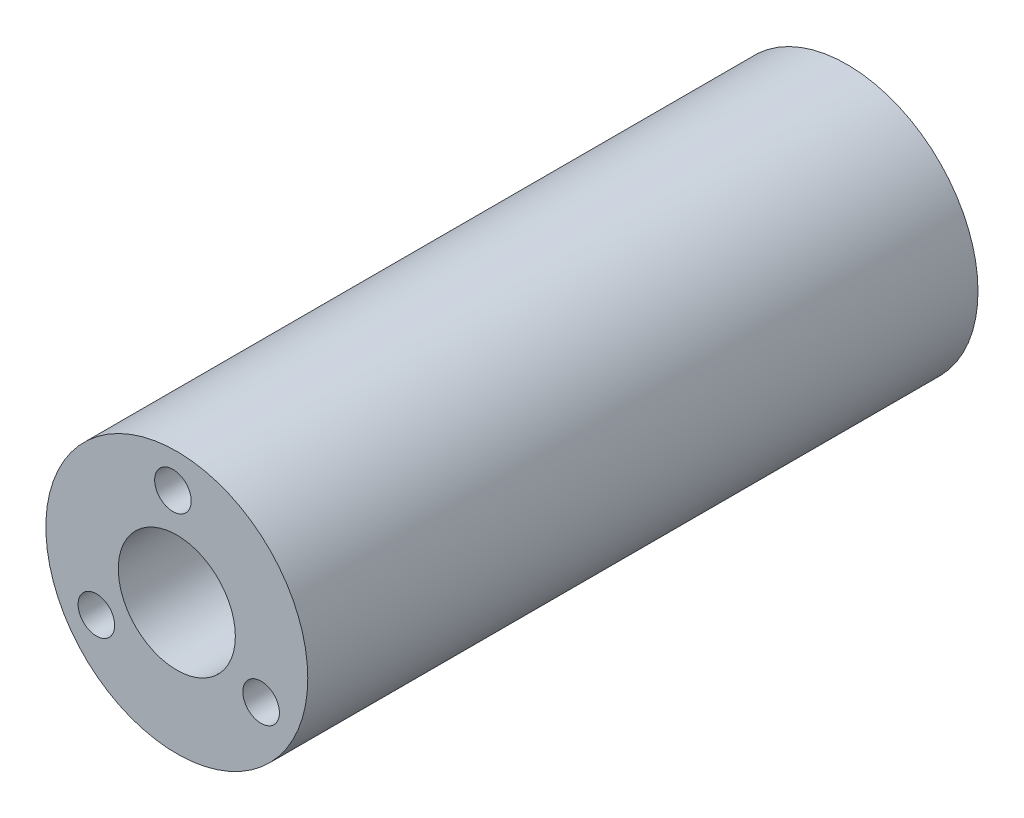
SolidWorks part; units mm, degrees
material "6061 Alloy"
ref_plane "Front Plane" through (0, 0, 0) normal (0, 0, 1) x (1, 0, 0)
ref_plane "Top Plane" through (0, 0, 0) normal (0, 1, 0) x (1, 0, 0)
ref_plane "Right Plane" through (0, 0, 0) normal (1, 0, 0) x (0, 0, -1)
sketch "Sketch1" plane through (0, 0, 0) normal (0, 0, 1) x (1, 0, 0)
  circle A0 centre (0, 0) radius 8.95
  circle A1 centre (-0.2651, 6.5) radius 1.25
  circle A2 centre (-5.4966, -3.4796) radius 1.25
  circle A3 centre (5.7617, -3.0204) radius 1.25
  circle A4 centre (0, 0) radius 4
  dimension "D1" = 17.9
  dimension "D2" = 2.5
  dimension "D3" = 8
extrude "Boss-Extrude1" add sketch "Sketch1" along normal blind 45.8
